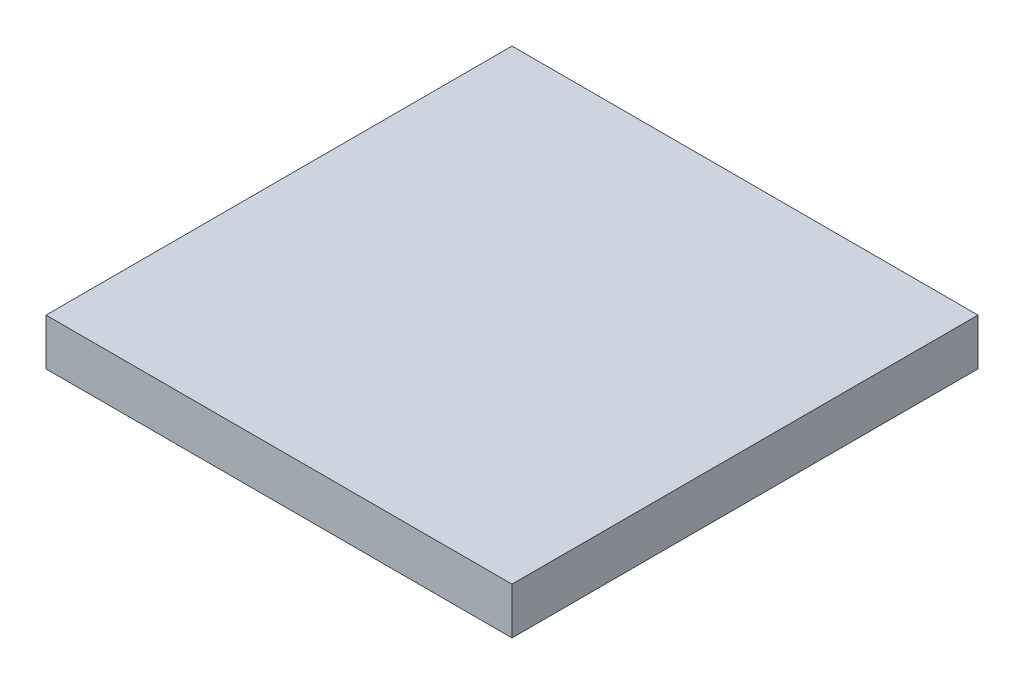
SolidWorks part; units mm, degrees
ref_plane "前视基准面" through (0, 0, 0) normal (0, 0, 1) x (1, 0, 0)
ref_plane "上视基准面" through (0, 0, 0) normal (0, 1, 0) x (1, 0, 0)
ref_plane "右视基准面" through (0, 0, 0) normal (1, 0, 0) x (0, 0, -1)
other "Configuration Table"
sketch "草图1" plane through (0, 0, 0) normal (0, 0, 1) x (1, 0, 0)
  line L0 (-5, 0) -> (5, 0)
extrude "Thin_0_0.001" add sketch "草图1" along normal blind 10 thin
